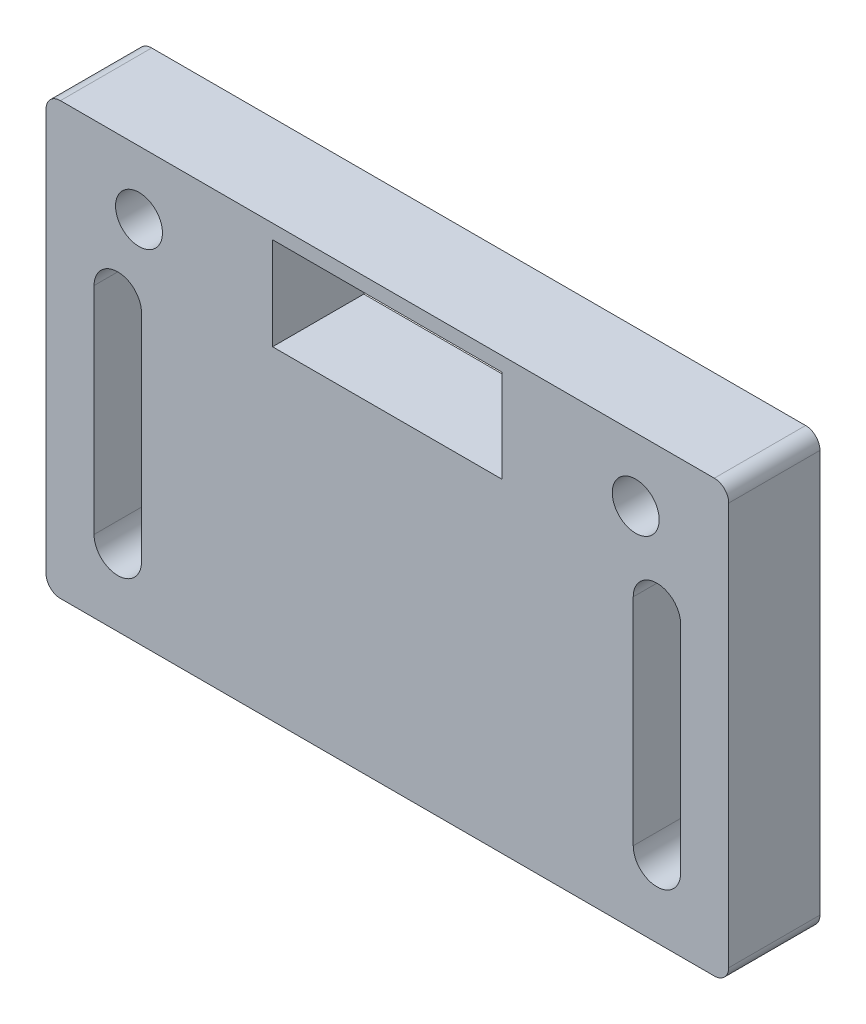
SolidWorks part; units mm, degrees
ref_plane "Front Plane" through (0, 0, 0) normal (0, 0, 1) x (1, 0, 0)
ref_plane "Top Plane" through (0, 0, 0) normal (0, 1, 0) x (1, 0, 0)
ref_plane "Right Plane" through (0, 0, 0) normal (1, 0, 0) x (0, 0, -1)
sketch "Sketch1" plane through (0, 0, 0) normal (0, 0, 1) x (1, 0, 0)
  line L0 (0, -2) -> (15.975, -2)
  line L1 (-47.5, 0) -> (47.5, 0)
  line L2 (-47.5, 0) -> (-47.5, -60)
  line L3 (-47.5, -60) -> (47.5, -60)
  line L4 (47.5, 0) -> (47.5, -60)
  line L5 (15.975, -2) -> (15.975, -14.9)
  line L6 (15.975, -14.9) -> (-15.975, -14.9)
  line L7 (-15.975, -14.9) -> (-15.975, -2)
  line L8 (-15.975, -2) -> (0, -2)
  line L9 (0, 0) -> (0, -2) construction
  dimension "D1" = 95
  dimension "D2" = 60
  dimension "D3" = 12.9
  dimension "D4" = 2
  dimension "D5" = 31.95
extrude "Boss-Extrude1" add sketch "Sketch1" along normal blind 12.7
sketch "Sketch2" plane through (0, 0, 0) normal (0, 0, -1) x (-1, 0, 0)
  line L0 (-47.5, -8.8451) -> (-34.56, -8.8451) construction
  line L1 (-47.5, -60) -> (-47.5, 0) construction
  line L2 (47.5, -8.8451) -> (34.56, -8.8451) construction
  line L3 (47.5, 0) -> (47.5, -60) construction
  line L4 (-34.56, -8.8451) -> (34.56, -8.8451) construction
  dimension "D1" = 69.12
hole_wizard "CSK for 1/4 Flat Head Machine Screw2" positions "Sketch5" profile "Sketch6" countersink size "1/4" standard "ANSI Inch" end condition through all
sketch "Sketch5" plane through (0, 0, 0) normal (0, 0, -1) x (-1, 0, 0)
  point P0 (-34.56, -8.8451)
  point P3 (34.56, -8.8451)
sketch "Sketch6" plane through (34.56, -8.8451, 0) normal (1, 0, 0) x (0, 1, 0)
  line L0 (0, 0) -> (0, 12.7)
  line L1 (0, 12.7) -> (3.2639, 12.7)
  line L2 (3.2639, 12.7) -> (3.2639, 3.6524)
  line L3 (3.2639, 3.6524) -> (6.4389, 0)
  line L5 (6.4389, 0) -> (0, 0)
  line L6 (-3.2639, 3.6524) -> (-6.4389, 0) construction
  line L11 (0, -6.35) -> (0, 107.95) construction
  dimension "Thru Hole Dia." = 6.5278
  dimension "Thru Hole Depth" = 12.7
  dimension "Near C'Sink Dia." = 12.8778
  dimension "Near C'Sink Angle" = 82
fillet "Fillet1" radius 2 2 edges at (-47.5, 0, 6.35) (-47.5, -60, 6.35)
fillet "Fillet2" radius 2 2 edges at (47.5, -60, 6.35) (47.5, 0, 6.35)
sketch "Sketch9" plane through (0, 0, 0) normal (0, 0, -1) x (-1, 0, 0)
  line L0 (-40.815, -19.9409) -> (-40.815, -49.9409)
  line L1 (-34.215, -49.9409) -> (-34.215, -19.9409)
  line L3 (-34.215, -40.8453) -> (34.215, -40.8453) construction
  line L4 (34.215, -49.9409) -> (34.215, -19.9409)
  line L5 (40.815, -49.9409) -> (40.815, -19.9409)
  line L6 (45.5, -60) -> (-45.5, -60) construction
  line L8 (-40.815, -34.9409) -> (-47.5, -34.9409)
  line L9 (-47.5, -58) -> (-47.5, -2) construction
  line L10 (40.815, -34.9409) -> (47.5, -34.9409)
  line L13 (47.5, -2) -> (47.5, -58) construction
  line L14 (0, 0) -> (0, -60) construction
  arc A0 (-34.215, -49.9409) -> (-40.815, -49.9409) centre (-37.515, -49.9409) cw
  arc A1 (-34.215, -19.9409) -> (-40.815, -19.9409) centre (-37.515, -19.9409) ccw
  arc A2 (34.215, -49.9409) -> (40.815, -49.9409) centre (37.515, -49.9409) ccw
  arc A3 (40.815, -19.9409) -> (34.215, -19.9409) centre (37.515, -19.9409) ccw
  dimension "D1" = 3.3
  dimension "D5" = 3.3
  dimension "D8" = 30
  dimension "D2" = 30
  dimension "D3" = 6.685
  dimension "D4" = 68.43
  dimension "D6" = 10.0591
  dimension "D7" = 10.0591
extrude "Cut-Extrude1" cut sketch "Sketch9" against normal through all contours L1 A1 L0 A0 | L5 A3 L4 A2
